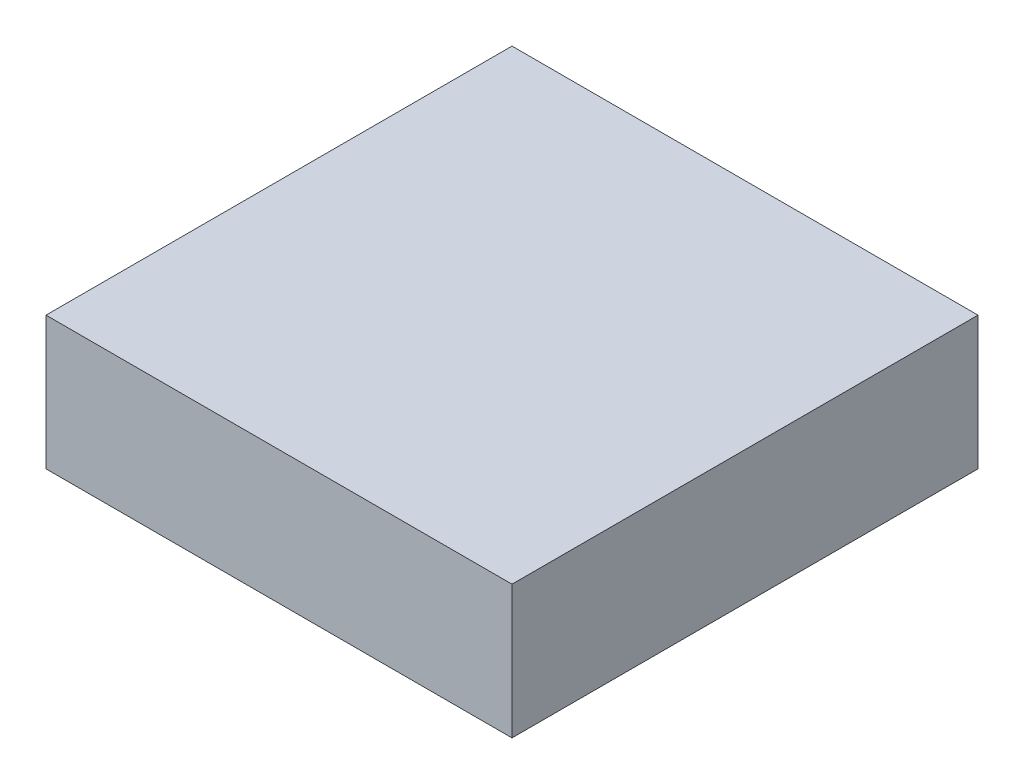
SolidWorks part; units mm, degrees
ref_plane "Front Plane" through (0, 0, 0) normal (0, 0, 1) x (1, 0, 0)
ref_plane "Top Plane" through (0, 0, 0) normal (0, 1, 0) x (1, 0, 0)
ref_plane "Right Plane" through (0, 0, 0) normal (1, 0, 0) x (0, 0, -1)
sketch "Sketch1" plane through (0, 0, 0) normal (0, 1, 0) x (1, 0, 0)
  line L1 (-35, 35) -> (35, 35)
  line L2 (-35, 35) -> (-35, -35)
  line L3 (-35, -35) -> (35, -35)
  line L4 (35, 35) -> (35, -35)
  line L5 (-35, 35) -> (35, -35) construction
  line L6 (-35, -35) -> (35, 35) construction
  point P0 (0, 0)
  dimension "D1" = 70
  dimension "D2" = 70
extrude "Boss-Extrude1" add sketch "Sketch1" along normal blind 20
sketch "Sketch2" plane through (0, 0, 0) normal (0, -1, 0) x (1, 0, 0)
  line L1 (-32.5, 32.5) -> (32.5, 32.5)
  line L2 (-32.5, 32.5) -> (-32.5, -32.5)
  line L3 (-32.5, -32.5) -> (32.5, -32.5)
  line L4 (32.5, 32.5) -> (32.5, -32.5)
  line L5 (-32.5, 32.5) -> (32.5, -32.5) construction
  line L6 (-32.5, -32.5) -> (32.5, 32.5) construction
  point P0 (0, 0)
  dimension "D1" = 65
  dimension "D2" = 65
extrude "Cut-Extrude1" cut sketch "Sketch2" against normal blind 15
